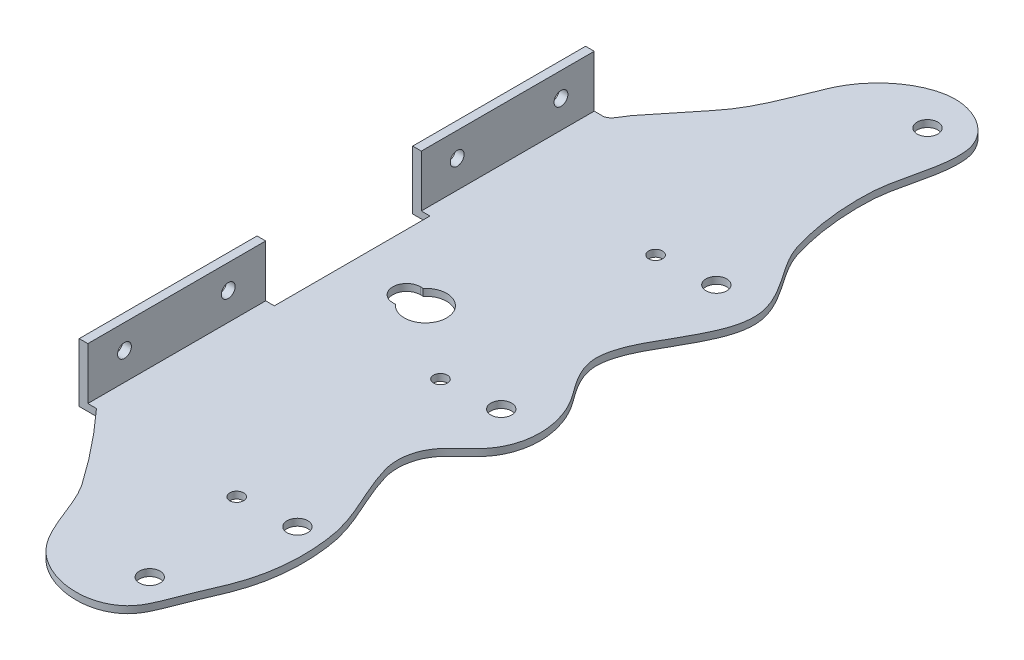
SolidWorks part; units mm, degrees
ref_plane "Alzado" through (0, 0, 0) normal (0, 0, 1) x (1, 0, 0)
ref_plane "Planta" through (0, 0, 0) normal (0, 1, 0) x (1, 0, 0)
ref_plane "Vista lateral" through (0, 0, 0) normal (1, 0, 0) x (0, 0, -1)
ref_plane "Plano1" through (0, 0, 0) normal (0, -1, 0) x (1, 0, 0)
sketch "Croquis1" plane through (0, 0, 0) normal (0, -1, 0) x (1, 0, 0)
  line L0 (404.2985, -1165.2643) -> (404.2985, -1311.6829)
  arc A0 (404.2985, -1165.2643) -> (421.4368, -1143.838) centre (255.6611, -1028.8056) ccw
  spline S0 degree 3 poles (404.2985, -1311.6829) (406.2956, -1311.7367) (407.085, -1314.4488) (409.5752, -1317.5435) (410.8203, -1319.0908) (414.5556, -1323.7328) (417.0649, -1326.8) (424.5132, -1336.3101) (426.8532, -1344.0451) (433.1714, -1358.7078) (440.2464, -1365.1551) (456.0885, -1368.0934) (464.9999, -1362.9326) (466.1658, -1346.9151) (462.4736, -1339.1903) (461.7627, -1323.2582) (462.7216, -1315.292) (467.1604, -1300.0675) (474.1763, -1294.5055) (477.9549, -1278.7237) (472.7345, -1270.9766) (465.1057, -1257.2725) (463.3269, -1252.4306) (464.7213, -1244.2656) (467.3242, -1240.8052) (474.8596, -1230.459) (476.349, -1220.8082) (469.7158, -1209.8114) (465.878, -1207.5713) (460.805, -1200.6115) (460.1335, -1195.934) (463.62, -1183.5494) (468.6543, -1176.2132) (471.5048, -1159.3523) (471.1045, -1150.5179) (466.8847, -1138.4173) (465.012, -1134.5734) (461.8421, -1126.6151) (460.6334, -1122.1798) (450.4899, -1114.2459) (439.6601, -1115.9446) (427.1441, -1127.1801) (426.028, -1136.6775) (421.4368, -1143.838) knots 0 0 0 0 0.015625 0.015625 0.03125 0.03125 0.0625 0.0625 0.125 0.125 0.1875 0.1875 0.25 0.25 0.3125 0.3125 0.375 0.375 0.4375 0.4375 0.5 0.5 0.53125 0.53125 0.5625 0.5625 0.625 0.625 0.65625 0.65625 0.6875 0.6875 0.75 0.75 0.8125 0.8125 0.84375 0.84375 0.875 0.875 0.9375 0.9375 1 1 1 1
extrude "Saliente-Extruir1" add sketch "Croquis1" against normal blind 2
sketch "Croquis2" plane through (404.2985, 0, 0) normal (-1, 0, 0) x (0, 0, 1)
  line L0 (-1311.6829, 2) -> (-1261.6829, 2)
  line L1 (-1261.6829, 2) -> (-1261.6829, 0)
  line L2 (-1261.6829, 0) -> (-1311.6829, 0)
  line L3 (-1311.6829, 0) -> (-1311.6829, 2)
extrude "Saliente-Extruir2" add sketch "Croquis2" along normal blind 5.0048
sketch "Croquis3" plane through (0, 2, 0) normal (0, 1, 0) x (-1, 0, 0)
  line L0 (-399.2937, -1261.6829) -> (-399.2937, -1311.6829)
  line L1 (-399.2937, -1311.6829) -> (-401.7961, -1311.6829)
  line L2 (-401.7961, -1311.6829) -> (-401.7961, -1261.6829)
  line L3 (-401.7961, -1261.6829) -> (-399.2937, -1261.6829)
extrude "Saliente-Extruir3" add sketch "Croquis3" along normal blind 15
sketch "Croquis4" plane through (404.2985, 0, 0) normal (-1, 0, 0) x (0, 0, 1)
  line L0 (-1216.6829, 2) -> (-1165.2643, 2)
  line L1 (-1165.2643, 2) -> (-1165.2643, 0)
  line L2 (-1165.2643, 0) -> (-1216.6829, 0)
  line L3 (-1216.6829, 0) -> (-1216.6829, 2)
extrude "Saliente-Extruir4" add sketch "Croquis4" along normal blind 5.0048
sketch "Croquis5" plane through (0, 2, 0) normal (0, 1, 0) x (-1, 0, 0)
  line L0 (-401.7961, -1165.2643) -> (-399.2937, -1165.2643)
  line L1 (-399.2937, -1165.2643) -> (-399.2937, -1216.6829)
  line L2 (-399.2937, -1216.6829) -> (-401.7961, -1216.6829)
  line L3 (-401.7961, -1216.6829) -> (-401.7961, -1165.2643)
extrude "Saliente-Extruir5" add sketch "Croquis5" along normal blind 15
sketch "Croquis6" plane through (0, 0, 0) normal (0, -1, 0) x (1, 0, 0)
  line L0 (426.2664, -1295.2212) -> (430.29, -1290.2547)
  line L1 (430.29, -1290.2547) -> (426.1062, -1275.6941)
  line L2 (426.1062, -1275.6941) -> (430.239, -1263.7367)
  line L3 (430.239, -1263.7367) -> (420.8071, -1267.1618)
  line L4 (420.8071, -1267.1618) -> (415.4015, -1278.732)
  line L5 (415.4015, -1278.732) -> (415.4015, -1299.9626)
  line L6 (415.4015, -1299.9626) -> (435.8281, -1316.511)
  line L7 (435.8281, -1316.511) -> (426.2664, -1295.2212)
extrude "Cortar-Extruir1" cut sketch "Croquis6" against normal through all
sketch "Croquis7" plane through (0, 0, 0) normal (0, -1, 0) x (1, 0, 0)
  line L0 (435.4785, -1159.0929) -> (415.4015, -1176.1451)
  line L1 (415.4015, -1176.1451) -> (415.4015, -1194.6262)
  line L2 (415.4015, -1194.6262) -> (420.3188, -1205.5749)
  line L3 (420.3188, -1205.5749) -> (428.973, -1207.5821)
  line L4 (428.973, -1207.5821) -> (426.1062, -1197.9604)
  line L5 (426.1062, -1197.9604) -> (429.3639, -1183.9148)
  line L6 (429.3639, -1183.9148) -> (424.6459, -1178.7172)
  line L7 (424.6459, -1178.7172) -> (435.4785, -1159.0929)
extrude "Cortar-Extruir2" cut sketch "Croquis7" against normal through all
sketch "Croquis8" plane through (0, 2, 0) normal (0, 1, 0) x (-1, 0, 0)
  line L0 (-420.6488, -1234.5863) -> (-421.4368, -1234.5863)
  line L1 (-421.4368, -1242.5863) -> (-420.6488, -1242.5863)
  arc A0 (-420.6488, -1242.5863) -> (-420.6488, -1234.5863) centre (-420.6488, -1238.5863) ccw
  arc A1 (-421.4368, -1234.5863) -> (-421.4368, -1242.5863) centre (-426.0897, -1238.5863) cw
extrude "Cortar-Extruir3" cut sketch "Croquis8" against normal through all
ref_plane "Plano2" through (0, 0, -1238.5863) normal (0, 0, 1) x (1, 0, 0)
sketch "Croquis9" plane through (0, 0, -1238.5863) normal (0, 0, 1) x (1, 0, 0)
  line L0 (432.2256, 2) -> (426.0897, 2)
  line L1 (426.0897, 2) -> (426.0897, 0)
  line L2 (426.0897, 0) -> (432.2256, 0)
  line L3 (432.2256, 0) -> (432.2256, 2)
  line L4 (426.0897, 2) -> (426.0897, 0) construction
revolve "Cortar-Revolución1" cut sketch "Croquis9" angle 360 about L4
hole_wizard "Diámetro de taladro Ø4.0 (4)1" positions "Croquis11" profile "Croquis10" hole size "Ø4.0" standard "Ansi Metric"
sketch "Croquis11" plane through (0, 2, 0) normal (0, 1, 0) x (1, 0, 0)
  point P0 (446.6597, 1222.362)
  point P1 (446.6597, 1284.5572)
  point P2 (446.6597, 1163.427)
sketch "Croquis10" plane through (446.6597, 2, -1222.362) normal (1, 0, 0) x (0, 0, 1)
  line L0 (0, 0) -> (0, 1)
  line L1 (0, 1) -> (2, 1)
  line L2 (2, 1) -> (2, 0)
  line L5 (2, 0) -> (0, 0)
  line L10 (0, 1) -> (-2, 1) construction
  line L11 (0, -6.35) -> (0, 107.95) construction
  dimension "Diámetro de taladro" = 4
  dimension "Profundidad de taladro" = 1
  dimension "Ángulo de perforador" = 180
hole_wizard "Diámetro de taladro Ø4.0 (4)2" positions "Croquis13" profile "Croquis12" hole size "Ø4.0" standard "Ansi Metric"
sketch "Croquis13" plane through (0, 0, 0) normal (0, -1, 0) x (-1, 0, 0)
  point P0 (-462.9399, 1223.6491)
  point P1 (-454.1975, 1130.7574)
  point P2 (-462.9399, 1285.8444)
  point P3 (-462.9399, 1164.7141)
  point P4 (-454.1975, 1355.6291)
sketch "Croquis12" plane through (462.9399, 0, -1223.6491) normal (1, 0, 0) x (0, 0, -1)
  line L0 (0, 0) -> (0, 17)
  line L1 (0, 17) -> (2, 17)
  line L2 (2, 17) -> (2, 0)
  line L5 (2, 0) -> (0, 0)
  line L11 (0, -6.35) -> (0, 107.95) construction
  dimension "Diámetro de taladro hasta el siguiente" = 4
  dimension "Profundidad de taladro hasta el siguiente" = 17
hole_wizard "Diámetro de taladro Ø4.0 (4)3" positions "Croquis15" profile "Croquis14" hole size "Ø4.0" standard "Ansi Metric"
sketch "Croquis15" plane through (401.7961, 0, 0) normal (1, 0, 0) x (0, 0, -1)
  point P0 (1272.0558, 10)
  point P1 (1302.0558, 10)
  point P2 (1175.8558, 10)
  point P3 (1205.8558, 10)
sketch "Croquis14" plane through (401.7961, 10, -1272.0558) normal (0, 1, 0) x (0, 0, -1)
  line L0 (0, 0) -> (0, 2.5024)
  line L1 (0, 2.5024) -> (2, 2.5024)
  line L2 (2, 2.5024) -> (2, 0)
  line L5 (2, 0) -> (0, 0)
  line L11 (0, -6.35) -> (0, 107.95) construction
  dimension "Diámetro de taladro hasta el siguiente" = 4
  dimension "Profundidad de taladro hasta el siguiente" = 2.5024
hole_wizard "Taladro de margen para M31" positions "Croquis17" profile "Croquis16" hole size "M3" standard "Ansi Metric"
sketch "Croquis17" plane through (0, 2, 0) normal (0, 1, 0) x (1, 0, 0)
  point P0 (419.2222, 1220.9802)
  point P1 (420.3188, 1227.8197)
  point P2 (419.2222, 1256.1924)
  point P3 (420.3188, 1249.3529)
  point P4 (426.7161, 1252.5284)
  point P5 (426.7161, 1224.6442)
sketch "Croquis16" plane through (419.2222, 2, -1220.9802) normal (1, 0, 0) x (0, 0, 1)
  line L0 (0, 0) -> (0, 2)
  line L1 (0, 2) -> (1.72, 2)
  line L2 (1.72, 2) -> (1.72, 0)
  line L5 (1.72, 0) -> (0, 0)
  line L11 (0, -6.35) -> (0, 107.95) construction
  dimension "Diámetro de taladro hasta el siguiente" = 3.44
  dimension "Profundidad de taladro hasta el siguiente" = 2
sketch "Croquis18" plane through (0, 2, 0) normal (0, 1, 0) x (-1, 0, 0)
  line L0 (-435.4785, -1159.0929) -> (-415.4015, -1176.1451)
  line L1 (-424.6459, -1178.7172) -> (-435.4785, -1159.0929)
  line L2 (-429.3639, -1183.9148) -> (-424.6459, -1178.7172)
  line L3 (-415.4015, -1176.1451) -> (-415.4015, -1194.6262)
  line L4 (-415.4015, -1194.6262) -> (-420.3188, -1205.5749)
  line L5 (-420.3188, -1205.5749) -> (-428.973, -1207.5821)
  line L6 (-428.973, -1207.5821) -> (-426.1062, -1197.9604)
  line L7 (-426.1062, -1197.9604) -> (-429.3639, -1183.9148)
  line L8 (-415.4015, -1299.9626) -> (-415.4015, -1278.732)
  line L9 (-415.4015, -1278.732) -> (-420.8071, -1267.1618)
  line L10 (-420.8071, -1267.1618) -> (-430.239, -1263.7367)
  line L11 (-430.239, -1263.7367) -> (-426.1062, -1275.6941)
  line L12 (-426.1062, -1275.6941) -> (-430.29, -1290.2547)
  line L13 (-430.29, -1290.2547) -> (-426.2664, -1295.2212)
  line L14 (-426.2664, -1295.2212) -> (-435.8281, -1316.511)
  line L15 (-435.8281, -1316.511) -> (-415.4015, -1299.9626)
  arc A0 (-419.2222, -1222.7002) -> (-419.2222, -1219.2602) centre (-419.2222, -1220.9802) ccw
  arc A1 (-419.2222, -1219.2602) -> (-419.2222, -1222.7002) centre (-419.2222, -1220.9802) ccw
  arc A2 (-426.7161, -1222.9242) -> (-426.7161, -1226.3642) centre (-426.7161, -1224.6442) ccw
  arc A3 (-426.7161, -1226.3642) -> (-426.7161, -1222.9242) centre (-426.7161, -1224.6442) ccw
  arc A4 (-420.3188, -1229.5397) -> (-420.3188, -1226.0997) centre (-420.3188, -1227.8197) ccw
  arc A5 (-420.3188, -1226.0997) -> (-420.3188, -1229.5397) centre (-420.3188, -1227.8197) ccw
  arc A6 (-420.3188, -1247.6329) -> (-420.3188, -1251.0729) centre (-420.3188, -1249.3529) ccw
  arc A7 (-420.3188, -1251.0729) -> (-420.3188, -1247.6329) centre (-420.3188, -1249.3529) ccw
  arc A8 (-419.2222, -1257.9124) -> (-419.2222, -1254.4724) centre (-419.2222, -1256.1924) ccw
  arc A9 (-419.2222, -1254.4724) -> (-419.2222, -1257.9124) centre (-419.2222, -1256.1924) ccw
  arc A10 (-426.7161, -1250.8084) -> (-426.7161, -1254.2484) centre (-426.7161, -1252.5284) ccw
  arc A11 (-426.7161, -1254.2484) -> (-426.7161, -1250.8084) centre (-426.7161, -1252.5284) ccw
extrude "Saliente-Extruir6" add sketch "Croquis18" against normal up to surface (2 mm away) up to face at (419.2222, 0, -1219.2602)
ref_plane "Plano3" through (0, 2, 0) normal (0, 1, 0) x (1, 0, 0)
sketch "Croquis24" plane through (0, 2, 0) normal (0, 1, 0) x (1, 0, 0)
  circle A0 centre (446.6597, 1284.5572) radius 2
  circle A1 centre (446.6597, 1222.362) radius 2
  circle A2 centre (446.6597, 1163.427) radius 2
  circle A3 centre (454.1975, 1130.7574) radius 3
  circle A4 centre (462.9399, 1164.7141) radius 3
  circle A5 centre (462.9399, 1223.6491) radius 3
  circle A6 centre (462.9399, 1285.8444) radius 3
  circle A7 centre (454.1975, 1355.6291) radius 3
extrude "Cortar-Extruir4" cut sketch "Croquis24" against normal blind 10
